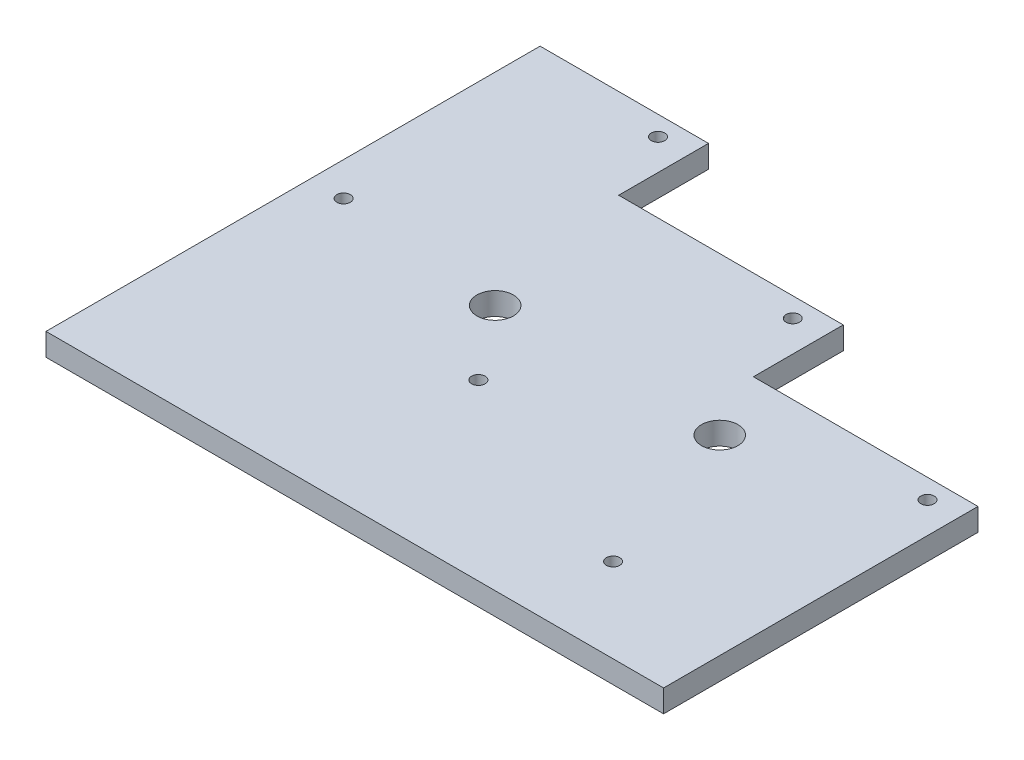
SolidWorks part; units mm, degrees
ref_plane "Front Plane" through (0, 0, 0) normal (0, 0, 1) x (1, 0, 0)
ref_plane "Top Plane" through (0, 0, 0) normal (0, 1, 0) x (1, 0, 0)
ref_plane "Right Plane" through (0, 0, 0) normal (1, 0, 0) x (0, 0, -1)
sketch "Sketch1" plane through (0, 0, 0) normal (0, 1, 0) x (1, 0, 0)
  line L0 (-87.3125, -69.85) -> (87.3125, -69.85)
  line L1 (87.3125, -69.85) -> (87.3125, 19.05)
  line L2 (87.3125, 19.05) -> (23.8125, 19.05)
  line L3 (23.8125, 19.05) -> (23.8125, 44.45)
  line L4 (23.8125, 44.45) -> (-39.6875, 44.45)
  line L5 (-39.6875, 44.45) -> (-39.6875, 69.85)
  line L6 (-39.6875, 69.85) -> (-87.3125, 69.85)
  line L7 (-87.3125, 69.85) -> (-87.3125, -69.85)
  point P8 (0, 0)
  dimension "D1" = 63.5
  dimension "D2" = 127
  dimension "D3" = 174.625
  dimension "D4" = 25.4
  dimension "D5" = 50.8
  dimension "D6" = 139.7
  dimension "D7" = 87.3125
  dimension "D8" = 69.85
extrude "Boss-Extrude1" add sketch "Sketch1" along normal mid plane 6.35
sketch "Sketch2" plane through (0, 0, 0) normal (0, 1, 0) x (1, 0, 0)
  circle A0 centre (-30.1625, 0) radius 5.1562
  circle A1 centre (33.3375, 0) radius 5.1562
  point P4 (0, 0)
  dimension "D1" = 10.3124
  dimension "D2" = 10.3124
  dimension "D3" = 63.5
  dimension "D4" = 30.1625
extrude "Cut-Extrude2" cut sketch "Sketch2" against normal through all from offset 3.175
sketch "Sketch3" plane through (0, 0, 0) normal (0, 1, 0) x (1, 0, 0)
  circle A0 centre (-77.7875, 4.7752) radius 1.8987
  circle A1 centre (-48.4251, 64.3128) radius 1.8987
  circle A2 centre (-14.2875, -20.6248) radius 1.8986
  circle A3 centre (15.0749, 38.9128) radius 1.8986
  circle A4 centre (49.2125, -46.0248) radius 1.8987
  circle A5 centre (78.5749, 13.5128) radius 1.8987
  point P12 (0, 0)
  dimension "D1" = 3.7973
  dimension "D2" = 3.7973
  dimension "D3" = 3.7973
  dimension "D4" = 3.7973
  dimension "D5" = 3.7973
  dimension "D6" = 3.7973
  dimension "D7" = 29.3624
  dimension "D8" = 63.5
  dimension "D9" = 92.8624
  dimension "D10" = 127
  dimension "D11" = 156.3624
  dimension "D12" = 25.4
  dimension "D13" = 50.8
  dimension "D14" = 59.5376
  dimension "D15" = 84.9376
  dimension "D16" = 110.3376
  dimension "D17" = 77.7875
  dimension "D18" = 46.0248
extrude "Cut-Extrude4" cut sketch "Sketch3" against normal blind 12.7 from offset 3.175
